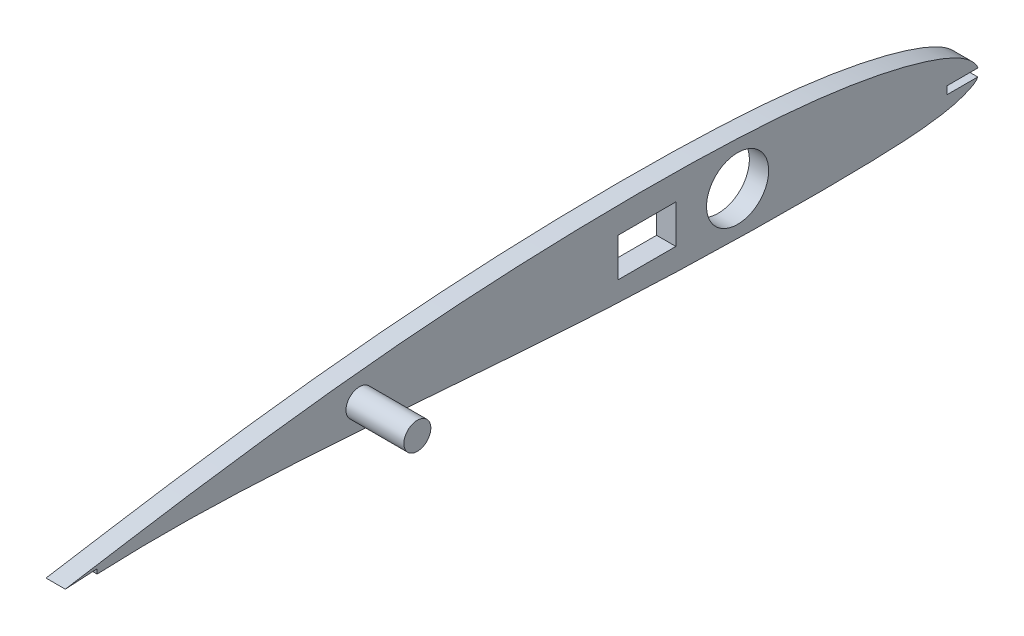
SolidWorks part; units mm, degrees
material "Manual Density from Real Component Centina"
ref_plane "Piano frontale" through (0, 0, 0) normal (0, 0, 1) x (1, 0, 0)
ref_plane "Piano superiore" through (0, 0, 0) normal (0, 1, 0) x (1, 0, 0)
ref_plane "Piano destro" through (0, 0, 0) normal (1, 0, 0) x (0, 0, -1)
curve "Curva1"
  spline degree 3 poles (0, 0.1724, 248.285) (0, -0.053, 250.4273) (0, 0.2462, 248.3284) (0, 0.5529, 246.6445) (0, 1.2459, 242.6221) (0, 2.0989, 237.7464) (0, 3.1818, 231.3634) (0, 4.2933, 223.9772) (0, 5.7312, 215.5604) (0, 7.1315, 206.3004) (0, 8.6324, 196.1631) (0, 10.1162, 185.3524) (0, 11.5493, 173.9891) (0, 12.8816, 162.1914) (0, 14.0593, 150.0724) (0, 15.0523, 137.7438) (0, 15.8256, 125.3116) (0, 16.3834, 112.8888) (0, 16.7267, 100.597) (0, 16.8648, 88.5669) (0, 16.792, 76.9314) (0, 16.4941, 65.8165) (0, 15.9609, 55.3329) (0, 15.1594, 45.573) (0, 14.0978, 36.6074) (0, 12.7884, 28.4972) (0, 11.2839, 21.2988) (0, 9.6413, 15.0749) (0, 7.9136, 9.8809) (0, 6.1182, 5.7699) (0, 4.2384, 2.7289) (0, 2.3057, 0.8126) (0, 0.7927, 0.0312) (0, -0.4105, -0.0213) (0, -1.7115, 0.4949) (0, -2.8658, 2.6253) (0, -4.0404, 5.6977) (0, -4.9287, 10.0719) (0, -5.5974, 15.6262) (0, -6.0122, 22.4122) (0, -6.265, 30.3619) (0, -6.3814, 39.3972) (0, -6.3554, 49.3987) (0, -6.2185, 60.2453) (0, -5.9476, 71.8018) (0, -5.5368, 83.9408) (0, -4.9386, 96.5461) (0, -4.1527, 109.5201) (0, -3.2196, 122.7671) (0, -2.1909, 136.1764) (0, -1.148, 149.6158) (0, -0.1602, 162.9314) (0, 0.706, 175.9537) (0, 1.3896, 188.4999) (0, 1.8332, 200.3712) (0, 1.9676, 211.3376) (0, 1.8232, 221.1842) (0, 1.4973, 229.6804) (0, 1.0741, 236.8065) (0, 0.6857, 242.1894) (0, 0.3087, 246.5181) (0, 0.1724, 248.285) (0, -0.053, 250.4273) (0, 0.2462, 248.3284) knots -0.014202 -0.006329 -0.001589 0 0.001576 0.006211 0.01368 0.023764 0.036307 0.051658 0.068045 0.086769 0.107053 0.128647 0.151303 0.174786 0.19886 0.223309 0.247929 0.272522 0.296848 0.320648 0.343669 0.365658 0.3864 0.405741 0.423561 0.439779 0.454311 0.467034 0.477831 0.486643 0.493542 0.498786 0.50271 0.50309 0.505896 0.510322 0.516831 0.525521 0.536535 0.549945 0.565696 0.583577 0.603379 0.624844 0.647727 0.671743 0.696673 0.722357 0.748609 0.77521 0.801891 0.828329 0.854175 0.879074 0.902636 0.924421 0.943939 0.960827 0.974827 0.985798 0.993671 0.998411 1 1.001576 1.006211 1.01368 periodic
sketch "Schizzo1" plane through (0, 0, 0) normal (1, 0, 0) x (0, 0, -1)
  line L0 (-250, 0) -> (0.0001, 0.0174) construction
  line L1 (0.0001, 0.0174) -> (-0.0034, 50.0174) construction
  line L2 (-62.4999, 16.3096) -> (-62.4999, -6.155) construction
  line L4 (-78.4999, 10.0773) -> (-93.4999, 10.0773)
  line L5 (-78.4999, 10.0773) -> (-78.4999, 0.0773)
  line L6 (-78.4999, 0.0773) -> (-93.4999, 0.0773)
  line L7 (-93.4999, 10.0773) -> (-93.4999, 0.0773)
  circle A0 centre (-62.4999, 5.0773) radius 8.05
  spline S0 degree 3 poles (-248.3284, 0.2462) (-250.4273, -0.053) (-248.285, 0.1724) (-246.5181, 0.3087) (-242.1894, 0.6857) (-236.8065, 1.0741) (-229.6804, 1.4973) (-221.1842, 1.8232) (-211.3376, 1.9676) (-200.3712, 1.8332) (-188.4999, 1.3896) (-175.9537, 0.706) (-162.9314, -0.1602) (-149.6158, -1.148) (-136.1764, -2.1909) (-122.7671, -3.2196) (-109.5201, -4.1527) (-96.5461, -4.9386) (-83.9408, -5.5368) (-71.8018, -5.9476) (-60.2453, -6.2185) (-49.3987, -6.3554) (-39.3972, -6.3814) (-30.3619, -6.265) (-22.4122, -6.0122) (-15.6262, -5.5974) (-10.0719, -4.9287) (-5.6977, -4.0404) (-2.6253, -2.8658) (-0.4949, -1.7115) (0.0213, -0.4105) (-0.0312, 0.7927) (-0.8126, 2.3057) (-2.7289, 4.2384) (-5.7699, 6.1182) (-9.8809, 7.9136) (-15.0749, 9.6413) (-21.2988, 11.2839) (-28.4972, 12.7884) (-36.6074, 14.0978) (-45.573, 15.1594) (-55.3329, 15.9609) (-65.8165, 16.4941) (-76.9314, 16.792) (-88.5669, 16.8648) (-100.597, 16.7267) (-112.8888, 16.3834) (-125.3116, 15.8256) (-137.7438, 15.0523) (-150.0724, 14.0593) (-162.1914, 12.8816) (-173.9891, 11.5493) (-185.3524, 10.1162) (-196.1631, 8.6324) (-206.3004, 7.1315) (-215.5604, 5.7312) (-223.9772, 4.2933) (-231.3634, 3.1818) (-237.7464, 2.0989) (-242.6221, 1.2459) (-246.6445, 0.5529) (-248.3284, 0.2462) (-250.4273, -0.053) (-248.285, 0.1724) knots -0.01368 -0.006211 -0.001576 0 0.001589 0.006329 0.014202 0.025173 0.039173 0.056061 0.075579 0.097364 0.120926 0.145825 0.171671 0.198109 0.22479 0.251391 0.277643 0.303327 0.328257 0.352273 0.375156 0.396621 0.416423 0.434304 0.450055 0.463465 0.474479 0.483169 0.489678 0.494104 0.49691 0.49729 0.501214 0.506458 0.513357 0.522169 0.532966 0.545689 0.560221 0.576439 0.594259 0.6136 0.634342 0.656331 0.679352 0.703152 0.727478 0.752071 0.776691 0.80114 0.825214 0.848697 0.871353 0.892947 0.913231 0.931955 0.948342 0.963693 0.976236 0.98632 0.993789 0.998424 1 1.001589 1.006329 1.014202 only from (-250, 0) to (-250, 0) construction
  spline S1 degree 3 poles (-248.3284, 0.2462) (-250.4273, -0.053) (-248.285, 0.1724) (-246.5181, 0.3087) (-242.1894, 0.6857) (-236.8065, 1.0741) (-229.6804, 1.4973) (-221.1842, 1.8232) (-211.3376, 1.9676) (-200.3712, 1.8332) (-188.4999, 1.3896) (-175.9537, 0.706) (-162.9314, -0.1602) (-149.6158, -1.148) (-136.1764, -2.1909) (-122.7671, -3.2196) (-109.5201, -4.1527) (-96.5461, -4.9386) (-83.9408, -5.5368) (-71.8018, -5.9476) (-60.2453, -6.2185) (-49.3987, -6.3554) (-39.3972, -6.3814) (-30.3619, -6.265) (-22.4122, -6.0122) (-15.6262, -5.5974) (-10.0719, -4.9287) (-5.6977, -4.0404) (-2.6253, -2.8658) (-0.4949, -1.7115) (0.0213, -0.4105) (-0.0312, 0.7927) (-0.8126, 2.3057) (-2.7289, 4.2384) (-5.7699, 6.1182) (-9.8809, 7.9136) (-15.0749, 9.6413) (-21.2988, 11.2839) (-28.4972, 12.7884) (-36.6074, 14.0978) (-45.573, 15.1594) (-55.3329, 15.9609) (-65.8165, 16.4941) (-76.9314, 16.792) (-88.5669, 16.8648) (-100.597, 16.7267) (-112.8888, 16.3834) (-125.3116, 15.8256) (-137.7438, 15.0523) (-150.0724, 14.0593) (-162.1914, 12.8816) (-173.9891, 11.5493) (-185.3524, 10.1162) (-196.1631, 8.6324) (-206.3004, 7.1315) (-215.5604, 5.7312) (-223.9772, 4.2933) (-231.3634, 3.1818) (-237.7464, 2.0989) (-242.6221, 1.2459) (-246.6445, 0.5529) (-248.3284, 0.2462) (-250.4273, -0.053) (-248.285, 0.1724) knots -0.01368 -0.006211 -0.001576 0 0.001589 0.006329 0.014202 0.025173 0.039173 0.056061 0.075579 0.097364 0.120926 0.145825 0.171671 0.198109 0.22479 0.251391 0.277643 0.303327 0.328257 0.352273 0.375156 0.396621 0.416423 0.434304 0.450055 0.463465 0.474479 0.483169 0.489678 0.494104 0.49691 0.49729 0.501214 0.506458 0.513357 0.522169 0.532966 0.545689 0.560221 0.576439 0.594259 0.6136 0.634342 0.656331 0.679352 0.703152 0.727478 0.752071 0.776691 0.80114 0.825214 0.848697 0.871353 0.892947 0.913231 0.931955 0.948342 0.963693 0.976236 0.98632 0.993789 0.998424 1 1.001589 1.006329 1.014202 only from (-250, 0) to (-250, 0)
  point P11 (-78.4999, 5.0773)
  dimension "D3" = 16.1
  dimension "D1" = 50
  dimension "D2" = 62.5
  dimension "D4" = 15
  dimension "D5" = 10
  dimension "D6" = 16
extrude "CorpoCentina" add sketch "Schizzo1" along normal blind 5
sketch "Schizzo2" plane through (0, 0, 0) normal (-1, 0, 0) x (0, 0, 1)
  circle A0 centre (160.4999, 6.0773) radius 3.5
  circle A1 centre (62.4999, 5.0773) radius 8.05 construction
  dimension "D1" = 7
  dimension "D2" = 98
  dimension "D3" = 1
extrude "PernoAggancio" add sketch "Schizzo2" along normal blind 15 and the other way blind 20
sketch "Schizzo3" plane through (-15, 0, 0) normal (-1, 0, 0) x (0, 0, 1)
  circle A0 centre (160.4999, 6.0773) radius 3.5
  circle A1 centre (160.4999, 6.0773) radius 3.5 construction
extrude "RimozionePernoSinistra" cut sketch "Schizzo3" against normal up to surface (15 mm away) up to face at (0, 6.0773, 163.9999)
sketch "Schizzo4" plane through (0, 0, 0) normal (-1, 0, 0) x (0, 0, 1)
  line L0 (0, 0) -> (62.4999, 5.0773) construction
  line L1 (-0.0001, 1) -> (8.1999, 1)
  line L6 (-0.0001, 1) -> (-0.0001, -1)
  line L7 (-0.0001, -1) -> (8.1999, -1)
  line L8 (8.1999, 1) -> (8.1999, -1)
  spline S1 degree 3 poles (248.285, 0.1724) (250.4273, -0.053) (248.3284, 0.2462) (246.6445, 0.5529) (242.6221, 1.2459) (237.7464, 2.0989) (231.3634, 3.1818) (223.9772, 4.2933) (215.5604, 5.7312) (206.3004, 7.1315) (196.1631, 8.6324) (185.3524, 10.1162) (173.9891, 11.5493) (162.1914, 12.8816) (150.0724, 14.0593) (137.7438, 15.0523) (125.3116, 15.8256) (112.8888, 16.3834) (100.597, 16.7267) (88.5669, 16.8648) (76.9314, 16.792) (65.8165, 16.4941) (55.3329, 15.9609) (45.573, 15.1594) (36.6074, 14.0978) (28.4972, 12.7884) (21.2988, 11.2839) (15.0749, 9.6413) (9.8809, 7.9136) (5.7699, 6.1182) (2.7289, 4.2384) (0.8126, 2.3057) (0.0312, 0.7927) (-0.0213, -0.4105) (0.4949, -1.7115) (2.6253, -2.8658) (5.6977, -4.0404) (10.0719, -4.9287) (15.6262, -5.5974) (22.4122, -6.0122) (30.3619, -6.265) (39.3972, -6.3814) (49.3987, -6.3554) (60.2453, -6.2185) (71.8018, -5.9476) (83.9408, -5.5368) (96.5461, -4.9386) (109.5201, -4.1527) (122.7671, -3.2196) (136.1764, -2.1909) (149.6158, -1.148) (162.9314, -0.1602) (175.9537, 0.706) (188.4999, 1.3896) (200.3712, 1.8332) (211.3376, 1.9676) (221.1842, 1.8232) (229.6804, 1.4973) (236.8065, 1.0741) (242.1894, 0.6857) (246.5181, 0.3087) (248.285, 0.1724) (250.4273, -0.053) (248.3284, 0.2462) knots -0.014202 -0.006329 -0.001589 0 0.001576 0.006211 0.01368 0.023764 0.036307 0.051658 0.068045 0.086769 0.107053 0.128647 0.151303 0.174786 0.19886 0.223309 0.247929 0.272522 0.296848 0.320648 0.343669 0.365658 0.3864 0.405741 0.423561 0.439779 0.454311 0.467034 0.477831 0.486643 0.493542 0.498786 0.50271 0.50309 0.505896 0.510322 0.516831 0.525521 0.536535 0.549945 0.565696 0.583577 0.603379 0.624844 0.647727 0.671743 0.696673 0.722357 0.748609 0.77521 0.801891 0.828329 0.854175 0.879074 0.902636 0.924421 0.943939 0.960827 0.974827 0.985798 0.993671 0.998411 1 1.001576 1.006211 1.01368 only from (250, 0) to (250, 0) construction
  point P7 (-0.0001, 0)
  dimension "D1" = 8.2
  dimension "D2" = 2
extrude "IntaglioAnteriore" cut sketch "Schizzo4" against normal through all
sketch "Schizzo5" plane through (0, 0, 0) normal (-1, 0, 0) x (0, 0, 1)
  line L0 (228.544, 2.7244) -> (228.4772, 1.5262)
  line L1 (228.4772, 1.5262) -> (236.6645, 1.07)
  line L2 (236.6645, 1.07) -> (236.7313, 2.2681)
  line L3 (236.7313, 2.2681) -> (228.544, 2.7244)
  line L4 (236.9504, 6.1995) -> (236.5227, -1.4763)
  line L5 (236.5227, -1.4763) -> (253.6946, -2.4332)
  line L6 (253.6946, -2.4332) -> (254.1223, 5.2427)
  line L7 (254.1223, 5.2427) -> (236.9504, 6.1995)
  spline S0 degree 3 poles (0.2015, 1) (0.3423, 1.3625) (1.0086, 2.5034) (2.7289, 4.2384) (5.7699, 6.1182) (9.8809, 7.9136) (15.0749, 9.6413) (21.2988, 11.2839) (28.4972, 12.7884) (36.6074, 14.0978) (45.573, 15.1594) (55.3329, 15.9609) (65.8165, 16.4941) (76.9314, 16.792) (88.5669, 16.8648) (100.597, 16.7267) (112.8888, 16.3834) (125.3116, 15.8256) (137.7438, 15.0523) (150.0724, 14.0593) (162.1914, 12.8816) (173.9891, 11.5493) (185.3524, 10.1162) (196.1631, 8.6324) (206.3004, 7.1315) (215.5604, 5.7312) (223.9772, 4.2933) (231.3634, 3.1818) (237.7464, 2.0989) (242.6221, 1.2459) (246.6445, 0.5529) (248.3284, 0.2462) (250.4273, -0.053) (248.285, 0.1724) (246.5181, 0.3087) (242.1894, 0.6857) (236.8065, 1.0741) (229.6804, 1.4973) (221.1842, 1.8232) (211.3376, 1.9676) (200.3712, 1.8332) (188.4999, 1.3896) (175.9537, 0.706) (162.9314, -0.1602) (149.6158, -1.148) (136.1764, -2.1909) (122.7671, -3.2196) (109.5201, -4.1527) (96.5461, -4.9386) (83.9408, -5.5368) (71.8018, -5.9476) (60.2453, -6.2185) (49.3987, -6.3554) (39.3972, -6.3814) (30.3619, -6.265) (22.4122, -6.0122) (15.6262, -5.5974) (10.0719, -4.9287) (5.6977, -4.0404) (2.6253, -2.8658) (0.8093, -1.8819) (0.3291, -1.1192) (0.2665, -1) knots 0.498933 0.498933 0.498933 0.498933 0.501214 0.506458 0.513357 0.522169 0.532966 0.545689 0.560221 0.576439 0.594259 0.6136 0.634342 0.656331 0.679352 0.703152 0.727478 0.752071 0.776691 0.80114 0.825214 0.848697 0.871353 0.892947 0.913231 0.931955 0.948342 0.963693 0.976236 0.98632 0.993789 0.998424 1 1.001589 1.006329 1.014202 1.025173 1.039173 1.056061 1.075579 1.097364 1.120926 1.145825 1.171671 1.198109 1.22479 1.251391 1.277643 1.303327 1.328257 1.352273 1.375156 1.396621 1.416423 1.434304 1.450055 1.463465 1.474479 1.483169 1.489678 1.494104 1.494882 1.494882 1.494882 1.494882 construction
  spline M12 degree 3 poles (248.285, 0.1724) (250.4273, -0.053) (248.3284, 0.2462) (246.6445, 0.5529) (242.6221, 1.2459) (237.7464, 2.0989) (231.3634, 3.1818) (223.9772, 4.2933) (215.5604, 5.7312) (206.3004, 7.1315) (196.1631, 8.6324) (185.3524, 10.1162) (173.9891, 11.5493) (162.1914, 12.8816) (150.0724, 14.0593) (137.7438, 15.0523) (125.3116, 15.8256) (112.8888, 16.3834) (100.597, 16.7267) (88.5669, 16.8648) (76.9314, 16.792) (65.8165, 16.4941) (55.3329, 15.9609) (45.573, 15.1594) (36.6074, 14.0978) (28.4972, 12.7884) (21.2988, 11.2839) (15.0749, 9.6413) (9.8809, 7.9136) (5.7699, 6.1182) (2.7289, 4.2384) (0.8126, 2.3057) (0.0312, 0.7927) (-0.0213, -0.4105) (0.4949, -1.7115) (2.6253, -2.8658) (5.6977, -4.0404) (10.0719, -4.9287) (15.6262, -5.5974) (22.4122, -6.0122) (30.3619, -6.265) (39.3972, -6.3814) (49.3987, -6.3554) (60.2453, -6.2185) (71.8018, -5.9476) (83.9408, -5.5368) (96.5461, -4.9386) (109.5201, -4.1527) (122.7671, -3.2196) (136.1764, -2.1909) (149.6158, -1.148) (162.9314, -0.1602) (175.9537, 0.706) (188.4999, 1.3896) (200.3712, 1.8332) (211.3376, 1.9676) (221.1842, 1.8232) (229.6804, 1.4973) (236.8065, 1.0741) (242.1894, 0.6857) (246.5181, 0.3087) (248.285, 0.1724) (250.4273, -0.053) (248.3284, 0.2462) knots -0.014202 -0.006329 -0.001589 0 0.001576 0.006211 0.01368 0.023764 0.036307 0.051658 0.068045 0.086769 0.107053 0.128647 0.151303 0.174786 0.19886 0.223309 0.247929 0.272522 0.296848 0.320648 0.343669 0.365658 0.3864 0.405741 0.423561 0.439779 0.454311 0.467034 0.477831 0.486643 0.493542 0.498786 0.50271 0.50309 0.505896 0.510322 0.516831 0.525521 0.536535 0.549945 0.565696 0.583577 0.603379 0.624844 0.647727 0.671743 0.696673 0.722357 0.748609 0.77521 0.801891 0.828329 0.854175 0.879074 0.902636 0.924421 0.943939 0.960827 0.974827 0.985798 0.993671 0.998411 1 1.001576 1.006211 1.01368 only from (0.2665, -1) to (0.2015, 1)
  dimension "D1" = 1.2
  dimension "D2" = 8.2
  dimension "D3" = 17.1719
  dimension "D4" = 7.6759
  dimension "D5" = 8.5874
extrude "IntaglioPosteriore" cut sketch "Schizzo5" against normal through all contours L2 L3 L0 M12 | L6 L7 L4 L5 M12 | L2 M12
